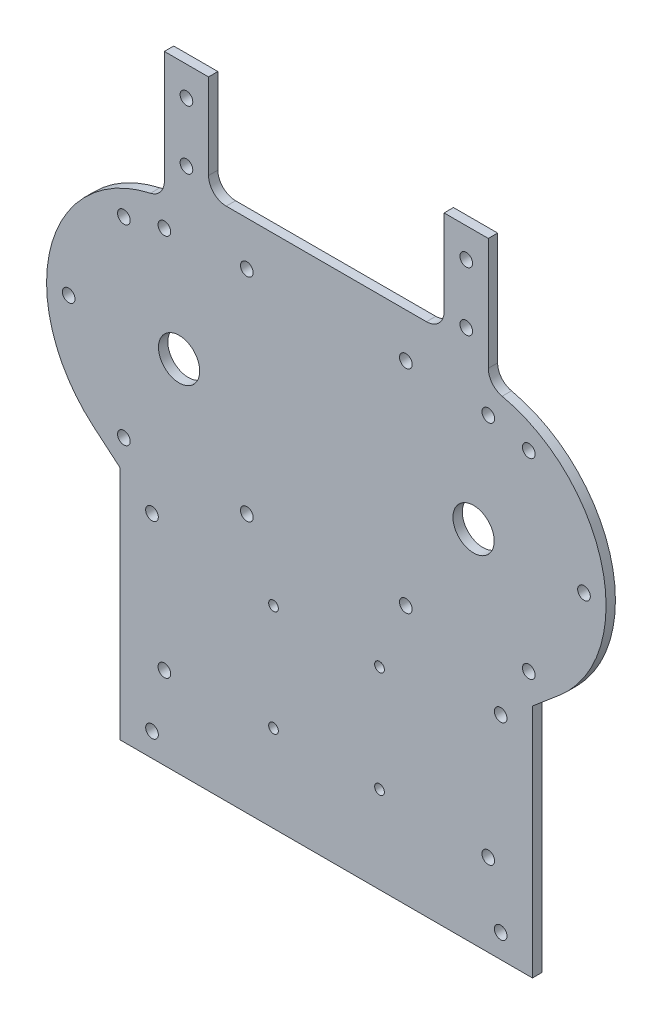
SolidWorks part; units mm, degrees
ref_plane "Front Plane" through (0, 0, 0) normal (0, 0, 1) x (1, 0, 0)
ref_plane "Top Plane" through (0, 0, 0) normal (0, 1, 0) x (1, 0, 0)
ref_plane "Right Plane" through (0, 0, 0) normal (1, 0, 0) x (0, 0, -1)
sketch "Sketch1" plane through (0, 0, 0) normal (0, 0, 1) x (1, 0, 0)
  line L1 (-100, -75) -> (100, -75)
  line L2 (-100, -75) -> (-100, 75)
  line L3 (-100, 75) -> (100, 75)
  line L4 (100, -75) -> (100, 75)
  line L5 (-100, -75) -> (100, 75) construction
  line L6 (-100, 75) -> (100, -75) construction
  line L8 (-47.5, 40) -> (47.5, 40) construction
  line L9 (0, 75) -> (0, -75) construction
  line L10 (-27, -52) -> (27, -52) construction
  line L11 (-27, -52) -> (-27, 20) construction
  line L12 (-27, 20) -> (27, 20) construction
  line L13 (27, -52) -> (27, 20) construction
  line L14 (-27, -52) -> (27, 20) construction
  line L15 (-27, 20) -> (27, -52) construction
  line L23 (-55, 70) -> (55, 70)
  line L24 (-55, 70) -> (-55, -70)
  line L25 (-55, -70) -> (55, -70)
  line L26 (55, 70) -> (55, -70)
  line L27 (-55, 70) -> (55, -70) construction
  line L28 (-55, -70) -> (55, 70) construction
  line L29 (-40, 70) -> (40, 70)
  line L30 (-40, 70) -> (-40, 35)
  line L31 (-40, 35) -> (40, 35)
  line L32 (40, 70) -> (40, 35)
  line L33 (-40, 70) -> (40, 35) construction
  line L34 (-40, 35) -> (40, 70) construction
  circle A2 centre (-47.5, 40) radius 2.15
  circle A3 centre (47.5, 40) radius 2.15
  circle A4 centre (-27, 20) radius 2.15
  circle A5 centre (27, 20) radius 2.15
  circle A6 centre (27, -52) radius 2.15
  circle A7 centre (-27, -52) radius 2.15
  circle A8 centre (-47.5, 60) radius 2.15
  circle A9 centre (47.5, 60) radius 2.15
  point P0 (0, 0)
  point P15 (0, 40)
  point P18 (0, -16)
  point P56 (0, 0)
  point P63 (0, 52.5)
  dimension "D3" = 4.3
  dimension "D4" = 20
  dimension "D5" = 4.3
  dimension "D8" = 4.3
  dimension "D1" = 150
  dimension "D2" = 200
  dimension "D6" = 72
  dimension "D7" = 54
  dimension "D14" = 30
  dimension "D15" = 140
  dimension "D16" = 110
  dimension "D17" = 95
  dimension "D18" = 20
  dimension "D19" = 35
  dimension "D20" = 80
extrude "Boss-Extrude1" add sketch "Sketch1" along normal blind 3.175 contours L23 L32 L31 L30 L24 L25 L26 A7 A6 A5 A4 A3 A2 | L2 L1 L4 L3
sketch "Sketch3" plane through (0, 0, 3.175) normal (0, 0, 1) x (1, 0, 0)
  line L0 (0, 0) -> (0, 95.843) construction
  line L1 (-50, -18) -> (-68.75, 14.476) construction
  line L2 (-50, -18) -> (-56.5118, 18.9303) construction
  line L3 (-50, -18) -> (-87.5, -18) construction
  circle A0 centre (-50, -18) radius 30 construction
  circle A1 centre (-50, -18) radius 45
  circle A2 centre (-50, -18) radius 37.5 construction
  circle A3 centre (-68.75, 14.476) radius 2.15
  circle A5 centre (-47.5, 40) radius 2.15 construction
  circle A7 centre (68.75, 14.476) radius 2.15
  circle A8 centre (50, -18) radius 45
  circle A9 centre (-87.5, -18) radius 2.15
  circle A10 centre (-68.75, -50.476) radius 2.15
  circle A11 centre (68.75, -50.476) radius 2.15
  circle A12 centre (87.5, -18) radius 2.15
  circle A13 centre (68.75, 14.476) radius 2.15
  dimension "D1" = 60
  dimension "D3" = 7.5
  dimension "D4" = 58
  dimension "D8" = 4.3
  dimension "D9" = 4.3
  dimension "D5" = 60
  dimension "D6" = 80
  dimension "D7" = 100
  dimension "D2" = 15
extrude "Boss-Extrude3" add sketch "Sketch3" against normal up to surface (3.175 mm away)
sketch "Sketch4" plane through (0, 0, 3.175) normal (0, 0, 1) x (1, 0, 0)
  line L1 (-60, -130) -> (-111.1989, -130)
  line L2 (-60, -130) -> (-60, -60)
  line L3 (-60, -60) -> (-38.9788, -60)
  line L4 (-70, -130) -> (-70, -60)
  line L5 (-60, -130) -> (-70, -60) construction
  line L6 (-60, -60) -> (-70, -130) construction
  line L10 (-111.1989, -130) -> (-70, -130)
  line L11 (-70, -60) -> (-79.0124, -52.3989)
  line L12 (-38.9788, -60) -> (-37.516, -61.2337)
  line L13 (-38.9788, -60) -> (-70, -60) construction
  line L14 (-70, -95) -> (-60, -95) construction
  line L15 (-60, -60) -> (-60, -95) construction
  line L18 (-60, -130) -> (-60, -122.95)
  line L22 (-60, -60) -> (65, -60)
  line L29 (-60, -60) -> (-60, -130)
  line L30 (-60, -130) -> (65, -130)
  line L31 (65, -60) -> (65, -130)
  line L32 (-60, -60) -> (65, -130) construction
  line L33 (-60, -130) -> (65, -60) construction
  line L34 (65, -130) -> (-70, -130)
  line L35 (65, -130) -> (65, -140)
  line L36 (65, -140) -> (-70, -140)
  line L37 (-70, -130) -> (-70, -140)
  line L38 (65, -130) -> (-70, -140) construction
  line L39 (65, -140) -> (-70, -130) construction
  arc A2 (-55, 26.7214) -> (-55, -62.7214) centre (-50, -18) ccw construction
  arc A3 (-37.516, -61.2337) -> (-79.0124, -52.3989) centre (-50, -18) cw
  circle A4 centre (-60, -65) radius 2.05 construction
  circle A6 centre (-60, -125) radius 2.05 construction
  point P0 (-65, -95)
  point P15 (-2.5, -135)
  point P31 (2.5, -95)
  point P36 (-87.5, -107.6256)
  dimension "D7" = 4.1
  dimension "D1" = 60
  dimension "D2" = 60
  dimension "D3" = 10
  dimension "D4" = 70
  dimension "D5" = 10
  dimension "D6" = 20
  dimension "D8" = 10
  dimension "D11" = 5
extrude "Boss-Extrude4" add sketch "Sketch4" against normal up to surface (3.175 mm away) up to face at (-24.85, 20, 0)
mirror "Mirror2" about plane through (0, 0, 0) normal (1, 0, 0) of "Boss-Extrude4"
fillet "Fillet1" radius 6 4 edges at (-55, 26.7214, 1.5875) (-40, 35, 1.5875) (40, 35, 1.5875) (55, 26.7214, 1.5875)
sketch "Sketch5" plane through (0, 0, 3.175) normal (0, 0, 1) x (1, 0, 0)
  circle A0 centre (-50, -18) radius 7
  circle A1 centre (50, -18) radius 7
  circle A5 centre (-50, -18) radius 45
  circle A6 centre (-50, -18) radius 45 construction
  circle A7 centre (50, -18) radius 45
  circle A8 centre (50, -18) radius 45 construction
  dimension "D1" = 14
  dimension "D3" = 0
  dimension "D4" = 0
extrude "Cut-Extrude1" cut sketch "Sketch5" against normal blind 10
sketch "Sketch6" plane through (0, 0, 3.175) normal (0, 0, 1) x (1, 0, 0)
  line L1 (-30, -72) -> (30, -72) construction
  line L2 (-30, -72) -> (-30, -113) construction
  line L3 (-30, -113) -> (30, -113) construction
  line L4 (30, -72) -> (30, -113) construction
  line L5 (-30, -72) -> (30, -113) construction
  line L6 (-30, -113) -> (30, -72) construction
  line L7 (-17.94, -74.5) -> (18.06, -74.5) construction
  line L8 (-17.94, -74.5) -> (-17.94, -110.5) construction
  line L9 (-17.94, -110.5) -> (18.06, -110.5) construction
  line L10 (18.06, -74.5) -> (18.06, -110.5) construction
  line L11 (-17.94, -74.5) -> (18.06, -110.5) construction
  line L12 (-17.94, -110.5) -> (18.06, -74.5) construction
  circle A0 centre (-17.94, -110.5) radius 1.65
  circle A1 centre (-17.94, -74.5) radius 1.65
  circle A2 centre (18.06, -74.5) radius 1.65
  circle A3 centre (18.06, -110.5) radius 1.65
  circle A4 centre (-27, -52) radius 2.15 construction
  point P4 (0, -92.5)
  point P9 (0.06, -92.5)
  dimension "D3" = 3.3
  dimension "D1" = 41
  dimension "D2" = 60
  dimension "D4" = 36
  dimension "D5" = 36
  dimension "D6" = 12.06
  dimension "D7" = 2.5
  dimension "D8" = 20
extrude "Cut-Extrude2" cut sketch "Sketch6" against normal blind 10
sketch "Sketch7" plane through (0, 0, 3.175) normal (0, 0, 1) x (1, 0, 0)
  line L1 (-55, 18) -> (55, 18) construction
  line L2 (-55, 18) -> (-55, -112) construction
  line L3 (-55, -112) -> (55, -112) construction
  line L4 (55, 18) -> (55, -112) construction
  line L5 (-55, 18) -> (55, -112) construction
  line L6 (-55, -112) -> (55, 18) construction
  circle A0 centre (-55, 18) radius 2.15
  circle A1 centre (55, 18) radius 2.15
  circle A2 centre (55, -112) radius 2.15
  circle A3 centre (-55, -112) radius 2.15
  circle A5 centre (-17.94, -74.5) radius 1.65 construction
  point P4 (0, -47)
  dimension "D1" = 4.3
  dimension "D3" = 37.5
  dimension "D2" = 130
  dimension "D4" = 110
extrude "Cut-Extrude3" cut sketch "Sketch7" against normal blind 10
sketch "Sketch8" plane through (0, 0, 3.175) normal (0, 0, 1) x (1, 0, 0)
  line L0 (-70, -60) -> (70, -60) construction
  line L1 (-70, -100) -> (70, -100) construction
  line L2 (-70, -140) -> (-70, -60) construction
  line L3 (70, -140) -> (70, -60) construction
  line L4 (0, -60) -> (0, -140) construction
  line L5 (70, -140) -> (-70, -140) construction
  line L7 (-70, -76) -> (-50, -76) construction
  line L8 (-70, -76) -> (-70, -60) construction
  line L9 (-70, -60) -> (-50, -60) construction
  line L10 (-50, -76) -> (-50, -60) construction
  line L11 (-70, -76) -> (-50, -60) construction
  line L12 (-70, -60) -> (-50, -76) construction
  circle A0 centre (-59.2, -68) radius 2.15
  circle A1 centre (-59.2, -132) radius 2.15
  circle A2 centre (59.2, -132) radius 2.15
  circle A3 centre (59.2, -68) radius 2.15
  point P14 (-60, -68)
  dimension "D3" = 4.3
  dimension "D1" = 20
  dimension "D2" = 16
  dimension "D4" = 10.8
  dimension "D5" = 8
extrude "Cut-Extrude4" cut sketch "Sketch8" against normal through all
